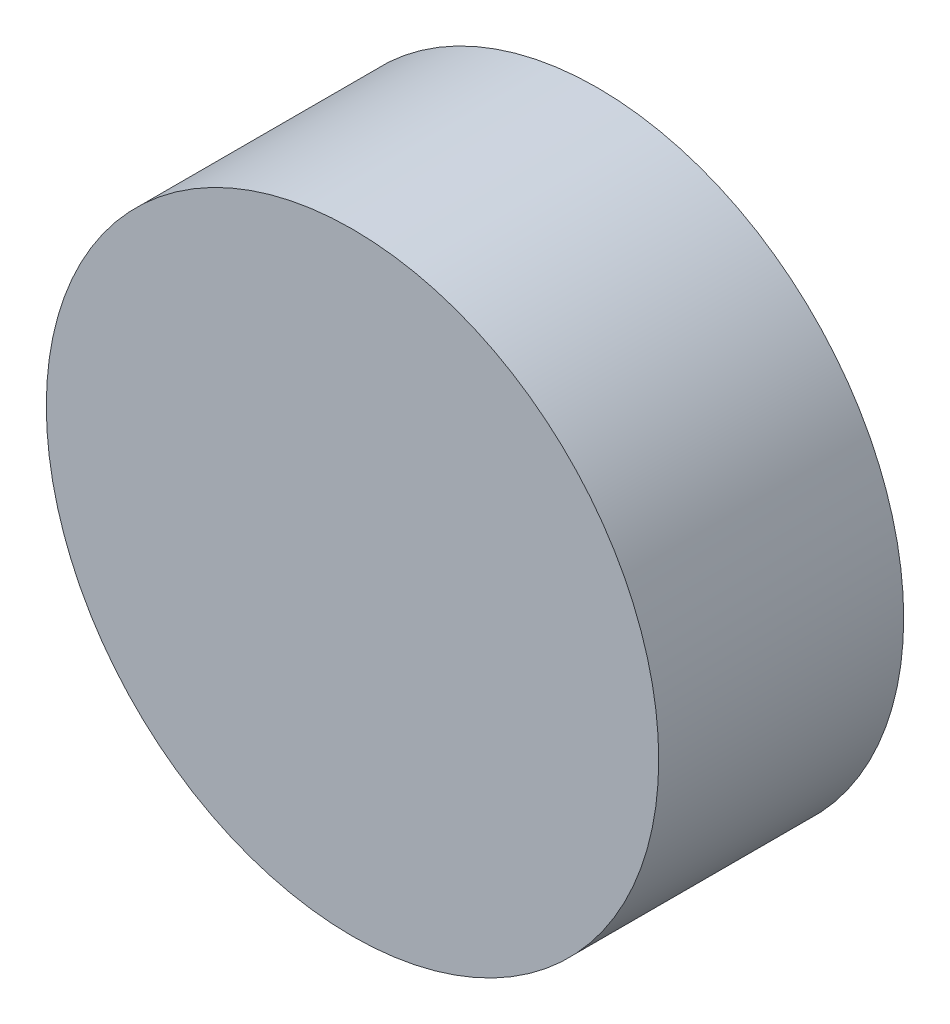
SolidWorks part; units mm, degrees
material "PET"
ref_plane "Front Plane" through (0, 0, 0) normal (0, 0, 1) x (1, 0, 0)
ref_plane "Top Plane" through (0, 0, 0) normal (0, 1, 0) x (1, 0, 0)
ref_plane "Right Plane" through (0, 0, 0) normal (1, 0, 0) x (0, 0, -1)
sketch "Sketch1" plane through (0, 0, 0) normal (0, 0, 1) x (1, 0, 0)
  circle A0 centre (0, 0) radius 20
extrude "Boss-Extrude1" add sketch "Sketch1" along normal blind 16
